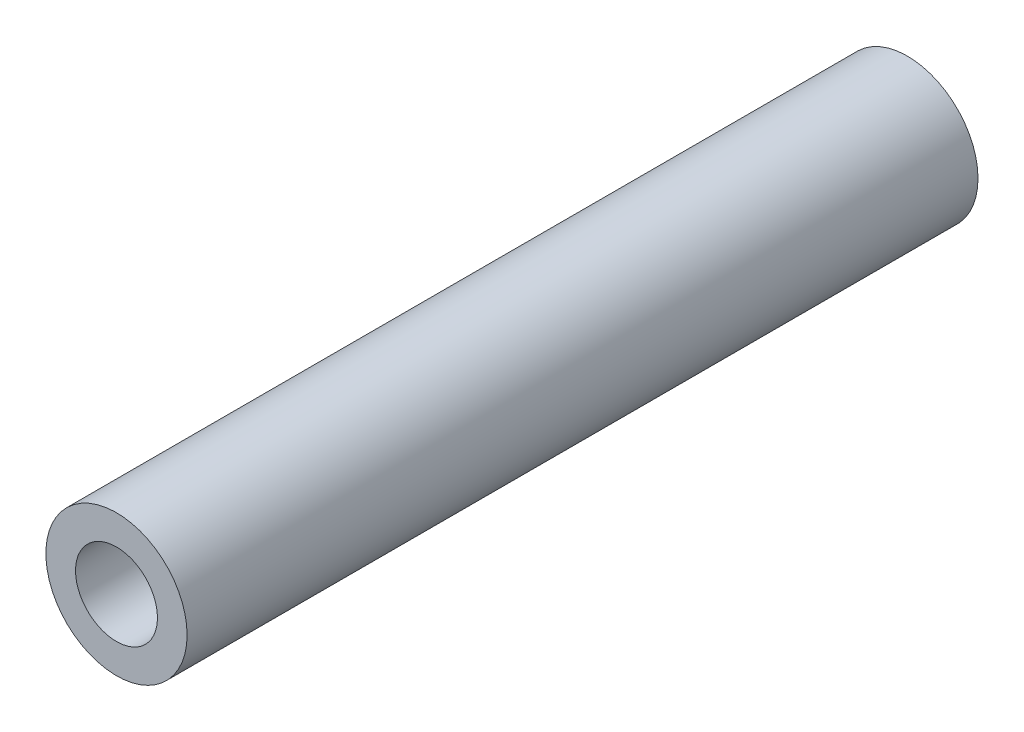
SolidWorks part; units mm, degrees
material "Polietileno reticulado"
ref_plane "Plano frontal" through (0, 0, 0) normal (0, 0, 1) x (1, 0, 0)
ref_plane "Plano superior" through (0, 0, 0) normal (0, 1, 0) x (1, 0, 0)
ref_plane "Plano direito" through (0, 0, 0) normal (1, 0, 0) x (0, 0, -1)
sketch "Esboço1" plane through (0, 0, 0) normal (0, 0, 1) x (1, 0, 0)
  circle A0 centre (0, 0) radius 5
  dimension "D1" = 10
extrude "Ressalto-extrusão1" add sketch "Esboço1" along normal blind 56
hole_wizard "Furo com folga de M51" positions "Esboço2" profile "Esboço3" hole size "M5" standard "ISO" end condition through all
sketch "Esboço2" plane through (0, 0, 0) normal (0, 0, -1) x (-1, 0, 0)
  point P0 (0, 0)
sketch "Esboço3" plane through (0, 0, 0) normal (1, 0, 0) x (0, 1, 0)
  line L0 (0, 0) -> (0, 56)
  line L1 (0, 56) -> (2.9, 56)
  line L2 (2.9, 56) -> (2.9, 0)
  line L5 (2.9, 0) -> (0, 0)
  line L11 (0, -6.35) -> (0, 107.95) construction
  dimension "Thru Hole Dia." = 5.8
  dimension "Thru Hole Depth" = 56
